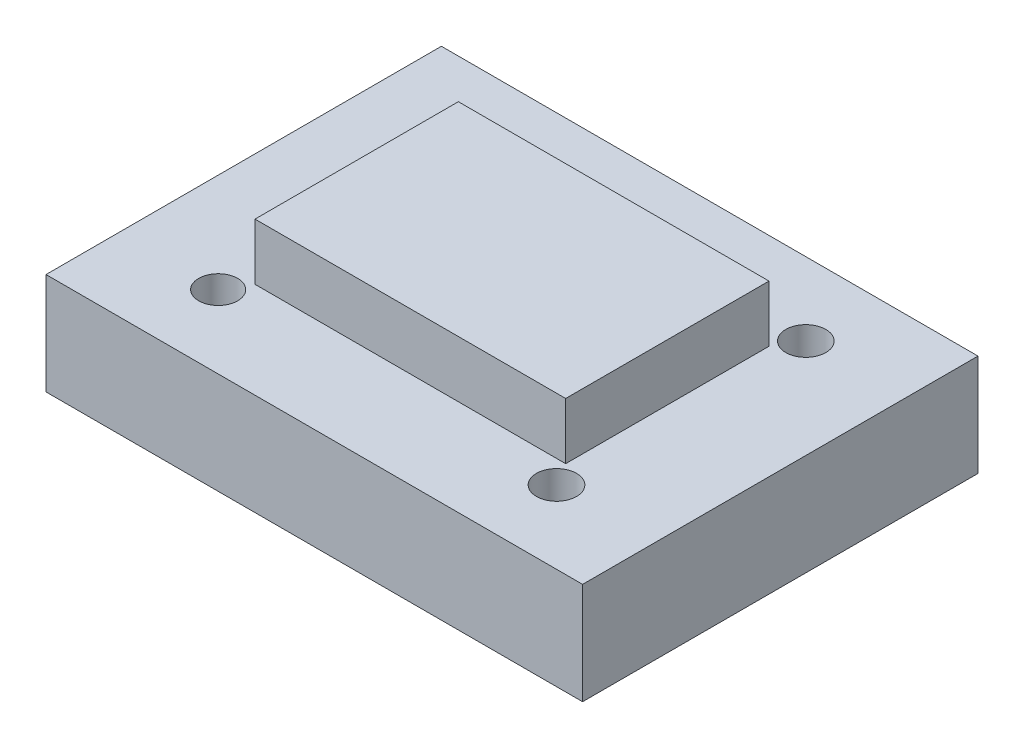
SolidWorks part; units mm, degrees
ref_plane "前视基准面" through (0, 0, 0) normal (0, 0, 1) x (1, 0, 0)
ref_plane "上视基准面" through (0, 0, 0) normal (0, 1, 0) x (1, 0, 0)
ref_plane "右视基准面" through (0, 0, 0) normal (1, 0, 0) x (0, 0, -1)
other "Configuration Table"
sketch "01_Base_Profile" plane through (0, 0, 0) normal (0, 1, 0) x (1, 0, 0)
  line L1 (-47.5, -35) -> (47.5, -35)
  line L2 (-47.5, -35) -> (-47.5, 35)
  line L3 (-47.5, 35) -> (47.5, 35)
  line L4 (47.5, -35) -> (47.5, 35)
  line L5 (-47.5, -35) -> (47.5, 35) construction
  line L6 (-47.5, 35) -> (47.5, -35) construction
  line L7 (-12.5, -14) -> (12.5, -14)
  line L8 (-12.5, -14) -> (-12.5, 14)
  line L9 (-12.5, 14) -> (12.5, 14)
  line L10 (12.5, -14) -> (12.5, 14)
  line L11 (-12.5, -14) -> (12.5, 14) construction
  line L12 (-12.5, 14) -> (12.5, -14) construction
  circle A0 centre (-29.9497, -22.0682) radius 3.4504
  circle A1 centre (29.9497, -22.0682) radius 3.5503
  circle A2 centre (-29.9497, 22.0682) radius 3.4504
  circle A3 centre (29.9497, 22.0682) radius 3.5503
  point P0 (0, 0)
  point P14 (0, 0)
extrude "01_Base_Extrude" add sketch "01_Base_Profile" along normal blind 18
sketch "02_Boss_Profile" plane through (0, 0, 0) normal (0, 1, 0) x (1, 0, 0)
  line L1 (-27.5, -18) -> (27.5, -18)
  line L2 (-27.5, -18) -> (-27.5, 18)
  line L3 (-27.5, 18) -> (27.5, 18)
  line L4 (27.5, -18) -> (27.5, 18)
  line L5 (-27.5, -18) -> (27.5, 18) construction
  line L6 (-27.5, 18) -> (27.5, -18) construction
  point P0 (0, 0)
extrude "02_Reinforcement_Boss" add sketch "02_Boss_Profile" along normal blind 28
